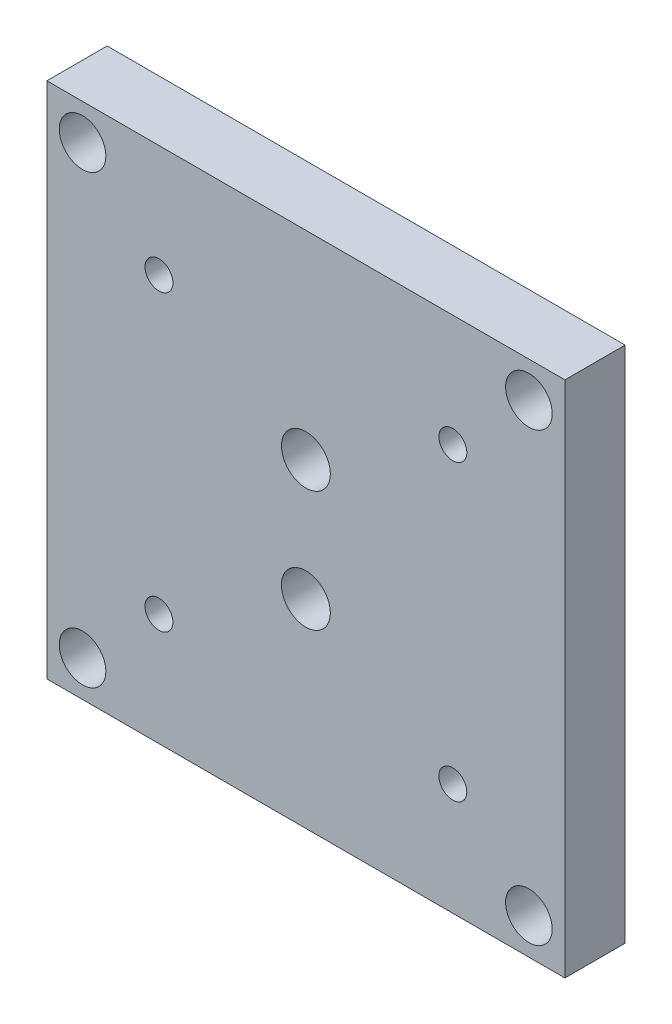
SolidWorks part; units mm, degrees
ref_plane "Front Plane" through (0, 0, 0) normal (0, 0, 1) x (1, 0, 0)
ref_plane "Top Plane" through (0, 0, 0) normal (0, 1, 0) x (1, 0, 0)
ref_plane "Right Plane" through (0, 0, 0) normal (1, 0, 0) x (0, 0, -1)
sketch "Sketch1" plane through (0, 0, 0) normal (0, 0, 1) x (1, 0, 0)
  line L1 (-27.305, 27.305) -> (27.305, 27.305)
  line L2 (-27.305, 27.305) -> (-27.305, -27.305)
  line L3 (-27.305, -27.305) -> (27.305, -27.305)
  line L4 (27.305, 27.305) -> (27.305, -27.305)
  dimension "D1" = 27.305
  dimension "D2" = 54.61
  dimension "D3" = 27.305
  dimension "D4" = 54.61
extrude "Boss-Extrude1" add sketch "Sketch1" along normal blind 6.35
hole_wizard "#10 (0.1935) Diameter Hole1" positions "Sketch5" profile "Sketch6" hole size "#10" standard "ANSI Inch" end condition through all
sketch "Sketch5" plane through (0, 0, 6.35) normal (0, 0, 1) x (1, 0, 0)
  line L0 (-27.305, 27.305) -> (-27.305, -27.305) construction
  line L2 (27.305, 27.305) -> (-27.305, 27.305) construction
  line L3 (-0.0175, 0.0175) -> (-23.5458, 23.5458) construction
  point P0 (-23.5458, 23.5458)
  point P21 (23.5107, 23.5458)
  point P22 (23.5107, -23.5107)
  point P23 (-23.5458, -23.5107)
  dimension "D1" = 3.7592
  dimension "D2" = 3.7592
  dimension "D4" = 33.274
  dimension "D3" = 4
sketch "Sketch6" plane through (-23.5458, 23.5458, 6.35) normal (1, 0, 0) x (0, -1, 0)
  line L0 (0, 0) -> (0, 6.35)
  line L1 (0, 6.35) -> (2.4574, 6.35)
  line L2 (2.4574, 6.35) -> (2.4574, 0)
  line L5 (2.4574, 0) -> (0, 0)
  line L11 (0, -6.35) -> (0, 107.95) construction
  dimension "Thru Hole Dia." = 4.9149
  dimension "Thru Hole Depth" = 6.35
hole_wizard "#32 (0.116) Diameter Hole1" positions "Sketch7" profile "Sketch8" hole size "#32" standard "ANSI Inch" end condition through all
sketch "Sketch7" plane through (0, 0, 6.35) normal (0, 0, 1) x (1, 0, 0)
  line L1 (27.305, 27.305) -> (-27.305, 27.305) construction
  line L2 (0, 0) -> (-15.4879, 15.494) construction
  line L3 (0, 6.35) -> (0, -6.35) construction
  circle A0 centre (0, 6.35) radius 2.5781
  circle A1 centre (0, -6.35) radius 2.5781
  point P0 (-15.4879, 15.494)
  point P16 (15.494, 15.4879)
  point P17 (15.4879, -15.494)
  point P18 (-15.494, -15.4879)
  dimension "D7" = 5.1562
  dimension "D8" = 5.1562
  dimension "D1" = 21.9075
  dimension "D2" = 11.811
  dimension "D3" = 4
  dimension "D4" = 21.9075
  dimension "D5" = 6.35
  dimension "D6" = 6.35
sketch "Sketch8" plane through (-15.4879, 15.494, 6.35) normal (1, 0, 0) x (0, -1, 0)
  line L0 (0, 0) -> (0, 6.35)
  line L1 (0, 6.35) -> (1.4732, 6.35)
  line L2 (1.4732, 6.35) -> (1.4732, 0)
  line L5 (1.4732, 0) -> (0, 0)
  line L11 (0, -6.35) -> (0, 107.95) construction
  dimension "Thru Hole Dia." = 2.9464
  dimension "Thru Hole Depth" = 6.35
sketch "Sketch10" plane through (0, 0, 0) normal (0, 0, 1) x (1, 0, 0)
  circle A0 centre (0, 6.35) radius 2.5781
  circle A1 centre (0, -6.35) radius 2.5781
  dimension "D1" = 5.1562
  dimension "D2" = 5.1562
  dimension "D3" = 6.35
  dimension "D4" = 6.35
extrude "Cut-Extrude1" cut sketch "Sketch10" along normal blind 6.35
